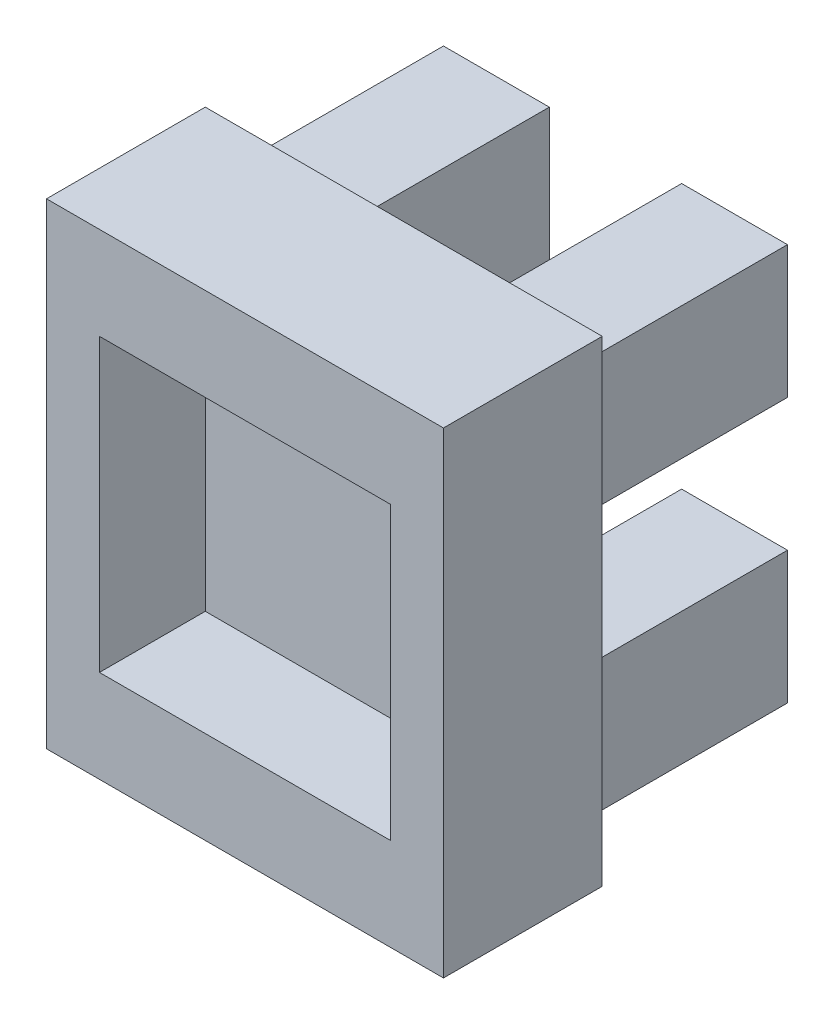
SolidWorks part; units mm, degrees
ref_plane "Front Plane" through (0, 0, 0) normal (0, 0, 1) x (1, 0, 0)
ref_plane "Top Plane" through (0, 0, 0) normal (0, 1, 0) x (1, 0, 0)
ref_plane "Right Plane" through (0, 0, 0) normal (1, 0, 0) x (0, 0, -1)
sketch "Sketch1" plane through (0, 0, 0) normal (0, 0, 1) x (1, 0, 0)
  line L1 (-7.5, -9) -> (7.5, -9)
  line L2 (-7.5, -9) -> (-7.5, 9)
  line L3 (-7.5, 9) -> (7.5, 9)
  line L4 (7.5, -9) -> (7.5, 9)
  line L5 (-7.5, -9) -> (7.5, 9) construction
  line L6 (-7.5, 9) -> (7.5, -9) construction
  point P0 (0, 0)
  dimension "D1" = 7.5
  dimension "D2" = 9
extrude "Boss-Extrude1" add sketch "Sketch1" along normal mid plane 6
sketch "Sketch2" plane through (0, 0, 3) normal (0, 0, 1) x (1, 0, 0)
  line L0 (7.5, -9) -> (7.5, 9) construction
  line L1 (-5.5, -5.5) -> (5.5, -5.5)
  line L2 (-5.5, -5.5) -> (-5.5, 5.5)
  line L3 (-5.5, 5.5) -> (5.5, 5.5)
  line L4 (5.5, -5.5) -> (5.5, 5.5)
  line L5 (-5.5, -5.5) -> (5.5, 5.5) construction
  line L6 (-5.5, 5.5) -> (5.5, -5.5) construction
  point P0 (0, 0)
  dimension "D1" = 2
extrude "Cut-Extrude1" cut sketch "Sketch2" against normal blind 4
sketch "Sketch4" plane through (0, 0, -3) normal (0, 0, -1) x (-1, 0, 0)
  line L1 (-6.5, 7.5) -> (-2.5, 7.5)
  line L2 (-6.5, 7.5) -> (-6.5, 2.5)
  line L3 (-6.5, 2.5) -> (-2.5, 2.5)
  line L4 (-2.5, 7.5) -> (-2.5, 2.5)
  line L7 (0, 3.3) -> (0, -3.3) construction
  line L8 (2.5, 7.5) -> (2.5, 2.5)
  line L9 (6.5, 2.5) -> (2.5, 2.5)
  line L10 (6.5, 7.5) -> (6.5, 2.5)
  line L11 (6.5, 7.5) -> (2.5, 7.5)
  line L12 (3.3, 0) -> (-3.3, 0) construction
  line L13 (6.5, -7.5) -> (2.5, -7.5)
  line L14 (6.5, -7.5) -> (6.5, -2.5)
  line L15 (6.5, -2.5) -> (2.5, -2.5)
  line L16 (2.5, -7.5) -> (2.5, -2.5)
  line L17 (-2.5, -7.5) -> (-2.5, -2.5)
  line L18 (-6.5, -2.5) -> (-2.5, -2.5)
  line L19 (-6.5, -7.5) -> (-6.5, -2.5)
  line L20 (-6.5, -7.5) -> (-2.5, -7.5)
  line L21 (-7.5, -9) -> (-7.5, 9) construction
  line L22 (7.5, -9) -> (-7.5, -9) construction
  dimension "D1" = 1
  dimension "D2" = 5
  dimension "D3" = 1.5
  dimension "D4" = 6.5
extrude "Boss-Extrude2" add sketch "Sketch4" along normal blind 8
